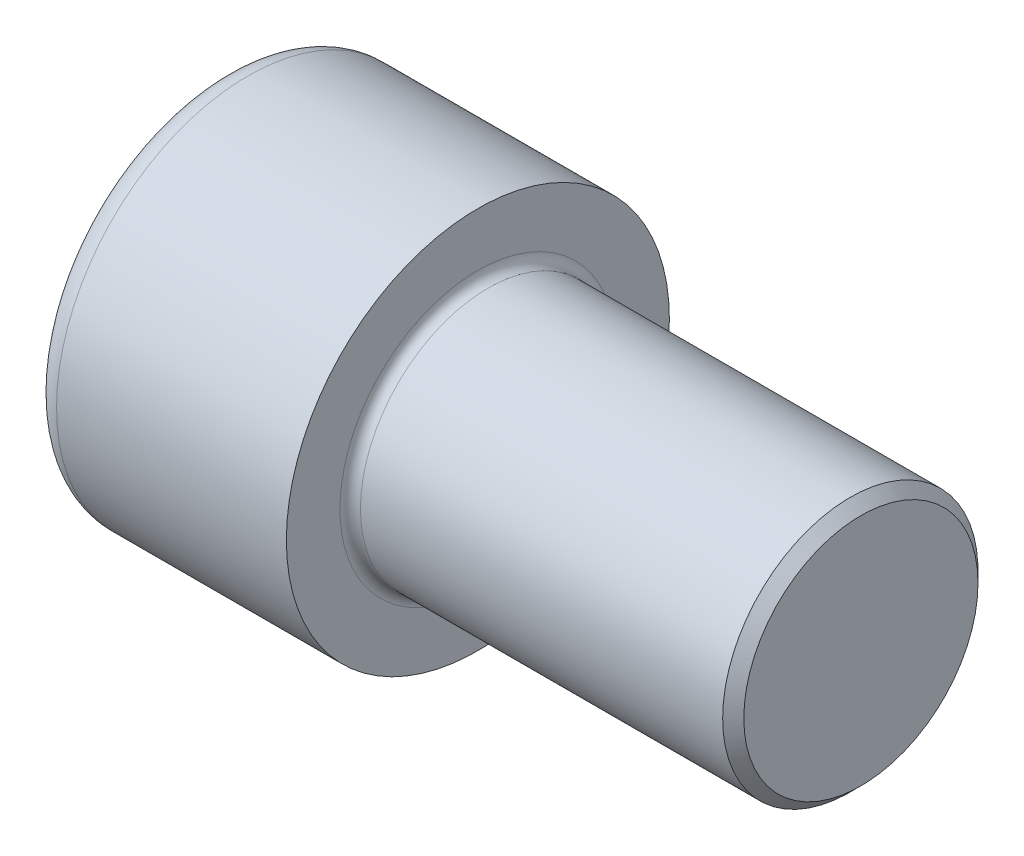
SolidWorks part; units mm, degrees
revolve "Base-Revolve" add sketch "BodySke"
sketch "BodySke" plane through (0, 0, 0) normal (0, 0, 1) x (1, 0, 0)
  line L0 (0, 0) -> (0, 15)
  line L1 (0, 15) -> (20, 15)
  line L2 (20, 15) -> (20, 10)
  line L3 (20, 10) -> (49.172, 10)
  line L4 (50, 9.172) -> (50, 0)
  line L5 (50, 0) -> (0, 0)
  line L6 (-31.75, 0) -> (127, 0) construction
  line L8 (50, 9.172) -> (49.172, 10)
  line L10 (50, -9.172) -> (49.172, -10) construction
  line L11 (21.5, 9.525) -> (21.5, 3.175) construction
  line L12 (20, 9.525) -> (20, 3.175) construction
  line L13 (-10, 9.525) -> (-10, 3.175) construction
  dimension "Head_ht" = 20
  dimension "Length" = 30
  dimension "Body_ch_ang" = 45
  dimension "Diameter" = 20
  dimension "Minor_dia" = 18.344
  dimension "Advance" = 1.5
  dimension "Thread_nom" = 30
  dimension "Thread_length" = 60
  dimension "Head_dia" = 30
cosmetic thread "ThreadCosmetic" [suppressed]
fillet "Fillet1" radius 0.8 1 edges at (20, 0, 10)
fillet "Fillet2" radius 2 1 edges at (0, 0, 15)
ref_plane "Plane1" through (0, 0, 0) normal (0, 0, 1) x (1, 0, 0)
ref_plane "Plane2" through (0, 0, 0) normal (0, 1, 0) x (1, 0, 0)
ref_plane "Plane3" through (0, 0, 0) normal (1, 0, 0) x (0, 0, -1)
sketch "Sketch2" plane through (0, 0, 0) normal (0, 0, 1) x (1, 0, 0)
  line L0 (0, 8.525) -> (10, 8.525)
  line L1 (10, 8.525) -> (14.9219, 0)
  line L2 (-31.75, 0) -> (127, 0) construction
  line L3 (14.9219, 0) -> (0, 0)
  line L4 (0, 0) -> (0, 8.525)
  line L6 (0, 0) -> (47.625, 0) construction
  dimension "D1" = 8.525
  dimension "D2" = 60
  dimension "Depth" = 10
revolve "Hex-PreBroach" cut sketch "Sketch2" angle 360 about L6
sketch "Sketch3" plane through (0, 0, 0) normal (-1, 0, 0) x (0, 0.5, 0.866)
  line L0 (4.9219, 8.525) -> (-4.9219, 8.525)
  line L1 (-4.9219, 8.525) -> (-9.8438, 0)
  line L2 (4.9219, 8.525) -> (9.8438, 0)
  line L3 (4.9219, -8.525) -> (9.8438, 0)
  line L4 (4.9219, -8.525) -> (-4.9219, -8.525)
  line L5 (-4.9219, -8.525) -> (-9.8438, 0)
  dimension "D1" = 8.525
  dimension "D2" = 8.525
  dimension "Hex_size" = 17.05
extrude "Hex" cut sketch "Sketch3" against normal blind 10
sketch "ThdSchSke" plane through (0, 0, 0) normal (0, 0, 1) x (1, 0, 0)
  line L0 (24.5, -9.172) -> (23.9202, -10)
  line L1 (24.5, -9.172) -> (25.0798, -10)
  line L2 (25.0798, -10) -> (25.0798, -12.5)
  line L3 (-3.175, 0) -> (5.1513, 0) construction
  line L4 (0, 13) -> (0, -13) construction
  line L5 (25.0798, -12.5) -> (23.9202, -12.5)
  line L6 (23.9202, -12.5) -> (23.9202, -10)
  dimension "Thread_minor" = 18.344
  dimension "Diameter" = 20
  dimension "Start" = 24.5
revolve "ThreadSchematic" [suppressed] cut sketch "ThdSchSke" angle 360 about L3
pattern_linear "ThdSchPat" [suppressed]
equation "\"D2@Sketch3\" = \"Hex_size@Sketch3\" / 2"
equation "\"D1@Sketch3\" = \"Hex_size@Sketch3\" / 2"
equation "\"D1@Sketch2\" = \"Hex_size@Sketch3\" / 2"
equation "\"Thread_minor@ThreadCosmetic\"  =  \"Minor_dia@BodySke\""
equation "\"Depth@Sketch2\" =  \"Key_eng@Hex\""
equation "\"Thread_length@ThreadCosmetic\" = ((sgn( (\"Length@BodySke\" - \"Advance@BodySke\" * 3.0) - \"Thread_nom@BodySke\" )-1)*( (\"Length@BodySke\" - \"Advance@BodySke\" * 3.0) - \"Thread_nom@BodySke\" ))/-2+ \"Thread_nom@BodySke\""
equation "\"Thread_minor@ThdSchSke\" = \"Minor_dia@BodySke\""
equation "\"Diameter@ThdSchSke\" = \"Diameter@BodySke\""
equation "\"Overcut@ThdSchSke\" = \"Diameter@BodySke\" * 1.25"
equation "\"Start@ThdSchSke\" = \"Head_ht@BodySke\" + \"Length@BodySke\" - \"Thread_length@ThreadCosmetic\"  '---Non-countersunk---"
equation "\"Num_threads@ThdSchPat\" = int( \"Thread_length@ThreadCosmetic\" / \"Advance@BodySke\" + 0.999 )  + 1"
equation "\"Advance@ThdSchPat\" = \"Thread_length@ThreadCosmetic\" /  (\"Num_threads@ThdSchPat\" - 1) 'relax it"
equation "\"Num_threads@ThdSchPat\" = \"Num_threads@ThdSchPat\" - sgn( \"Num_threads@ThdSchPat\" - 1) '---chamfered tips only---"
